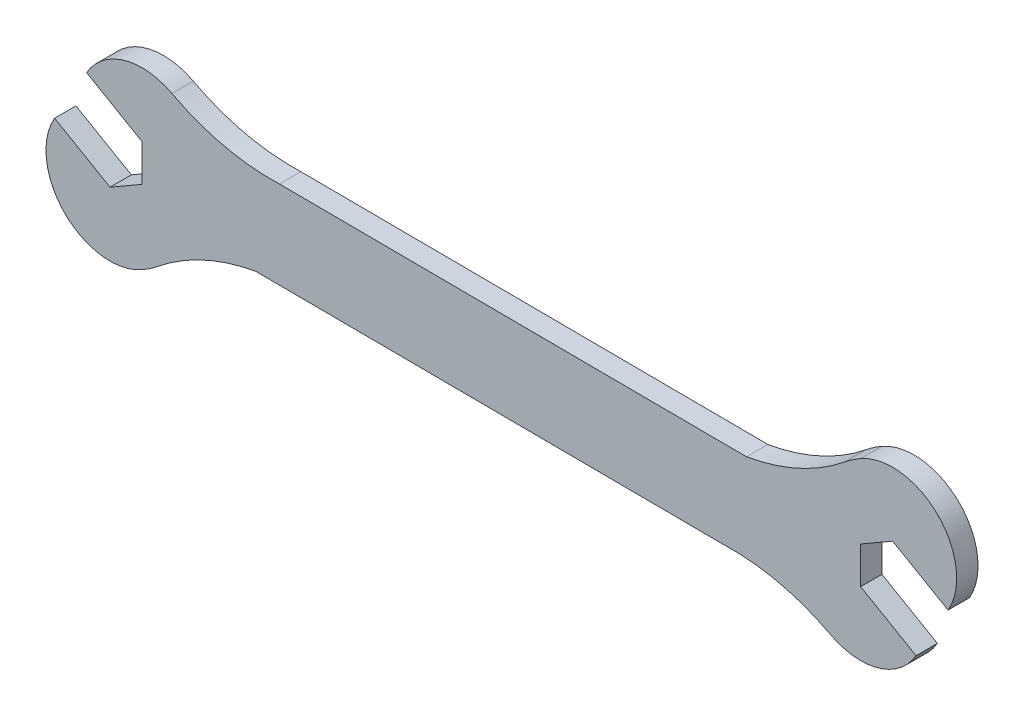
SolidWorks part; units mm, degrees
ref_plane "Front Plane" through (0, 0, 0) normal (0, 0, 1) x (1, 0, 0)
ref_plane "Top Plane" through (0, 0, 0) normal (0, 1, 0) x (1, 0, 0)
ref_plane "Right Plane" through (0, 0, 0) normal (1, 0, 0) x (0, 0, -1)
sketch "Sketch1" plane through (0, 0, 0) normal (0, 0, 1) x (1, 0, 0)
  line L0 (0, 0) -> (185, 0) construction
  line L1 (0, 0) -> (0, 14.9669) construction
  line L2 (0, 0) -> (0, -15) construction
  line L3 (0, 14.9669) -> (0, 30) construction
  line L4 (0, -15) -> (0, -30) construction
  line L5 (0, 0) -> (-37.2571, 0) construction
  line L6 (0, 0) -> (-36.2882, 20.951) construction
  line L7 (0, 0) -> (31.792, -18.3551) construction
  line L8 (0, 14.9669) -> (-61.1397, 14.9669) construction
  line L9 (77.979, -8.6603) -> (77.979, 93.4614) construction
  line L10 (77.979, -8.6603) -> (77.979, -82.5631) construction
  line L11 (0, 14.9669) -> (185, 14.9669) construction
  line L12 (0, 8.6603) -> (-19.6523, 20.0065) construction
  line L13 (7.5, -4.3301) -> (7.5, 4.3301)
  line L14 (7.5, 4.3301) -> (0, 8.6603)
  line L17 (-7.5, -4.3301) -> (0, -8.6603)
  line L18 (0, -8.6603) -> (7.5, -4.3301)
  line L19 (-7.5, -4.3301) -> (-27.1523, 7.0161) construction
  line L20 (0, -8.6603) -> (19.2156, -8.6603) construction
  line L21 (17.3101, -8.6603) -> (17.3101, 11.8301) construction
  line L22 (19.2156, -8.6603) -> (77.979, -8.6603) construction
  line L23 (0, -8.6603) -> (-12.3205, -30) construction
  line L24 (7.5, 4.3301) -> (22.5, 30.3109) construction
  line L25 (0, 8.6603) -> (-3.75, 6.4952) [skipped]
  line L26 (-7.5, 0) -> (-7.5, -4.3301) [skipped]
  line L27 (-5.4904, 11.8301) -> (0, 8.6603)
  line L28 (-7.5, -4.3301) -> (-12.9904, -1.1603)
  line L29 (0, 0) -> (11.2259, -27.8205) construction
  line L30 (17.3101, 11.8301) -> (67.0112, 11.8301) construction
  line L31 (34.2162, -8.6603) -> (34.2162, 11.9311) construction
  line L32 (183.2959, 2.5347) -> (183.2959, -12.4323) construction
  line L33 (183.2959, 2.5347) -> (183.2959, 17.5347) construction
  line L34 (183.2959, -12.4323) -> (183.2959, -27.4653) construction
  line L35 (183.2959, 17.5347) -> (183.2959, 32.5347) construction
  line L36 (183.2959, 2.5347) -> (220.553, 2.5347) construction
  line L37 (183.2959, 2.5347) -> (219.5841, -18.4163) construction
  line L38 (183.2959, 2.5347) -> (151.5039, 20.8898) construction
  line L39 (183.2959, -6.1256) -> (202.9481, -17.4718) construction
  line L40 (175.7959, 6.8648) -> (175.7959, -1.7955)
  line L41 (175.7959, -1.7955) -> (183.2959, -6.1256)
  line L42 (190.7959, 6.8648) -> (183.2959, 11.1949)
  line L43 (183.2959, 11.1949) -> (175.7959, 6.8648)
  line L44 (190.7959, 6.8648) -> (210.4481, -4.4814) construction
  line L45 (183.2959, 11.1949) -> (164.0802, 11.1949) construction
  line L46 (165.9857, 11.1949) -> (165.9857, -9.2955) construction
  line L47 (183.2959, 11.1949) -> (195.6164, 32.5347) construction
  line L48 (175.7959, -1.7955) -> (160.7959, -27.7762) construction
  line L49 (188.7862, -9.2955) -> (183.2959, -6.1256)
  line L50 (190.7959, 6.8648) -> (196.2862, 3.6949)
  line L51 (183.2959, 2.5347) -> (172.07, 30.3552) construction
  line L52 (149.0796, 11.1949) -> (149.0796, -9.3965) construction
  line L53 (67.0112, 11.8301) -> (158.7448, 11.8301) construction
  line L54 (77.979, -8.6603) -> (150.7838, -8.6603) construction
  line L55 (39.6865, 11.8301) -> (149.0796, 11.1949)
  line L56 (143.6094, -9.2955) -> (34.2162, -8.6603)
  arc A3 (-3.75, -6.4952) -> (3.75, 6.4952) centre (0, 0) ccw construction
  arc A4 (-2.0917, -7.2024) -> (0, -8.6603) centre (7.5, 4.3301) ccw
  arc A5 (-12.9904, -1.1603) -> (8.4856, -21.0294) centre (0, -8.6603) ccw
  arc A6 (7.5, 4.3301) -> (5.1916, 5.4127) centre (0, -8.6603) ccw
  arc A7 (22.5, 4.3301) -> (-5.4904, 11.8301) centre (7.5, 4.3301) ccw
  arc A9 (7.5, -21.6506) -> (22.5, 4.3301) centre (-7.5, 4.3301) ccw
  arc A10 (34.2162, -8.6603) -> (8.6245, -21.3735) centre (42.7378, -57.9287) ccw
  arc A12 (14.5092, 17.5918) -> (39.6865, 11.8301) centre (37.8732, 61.7972) ccw
  arc A13 (187.0459, 9.0299) -> (179.5459, -3.9605) centre (183.2959, 2.5347) ccw construction
  arc A14 (185.3875, 9.7371) -> (183.2959, 11.1949) centre (175.7959, -1.7955) ccw
  arc A15 (196.2862, 3.6949) -> (174.8103, 23.564) centre (183.2959, 11.1949) ccw
  arc A16 (175.7959, -1.7955) -> (178.1042, -2.878) centre (183.2959, 11.1949) ccw
  arc A17 (160.7959, -1.7955) -> (188.7862, -9.2955) centre (175.7959, -1.7955) ccw
  arc A18 (175.7959, 24.1853) -> (160.7959, -1.7955) centre (190.7959, -1.7955) ccw
  arc A19 (149.0796, 11.1949) -> (174.6714, 23.9082) centre (140.5581, 60.4634) ccw
  arc A20 (168.7867, -15.0571) -> (143.6094, -9.2955) centre (145.4227, -59.2626) ccw
  dimension "D1" = 30
  dimension "D2" = 30
extrude "Boss-Extrude1" add sketch "Sketch1" along normal blind 5
